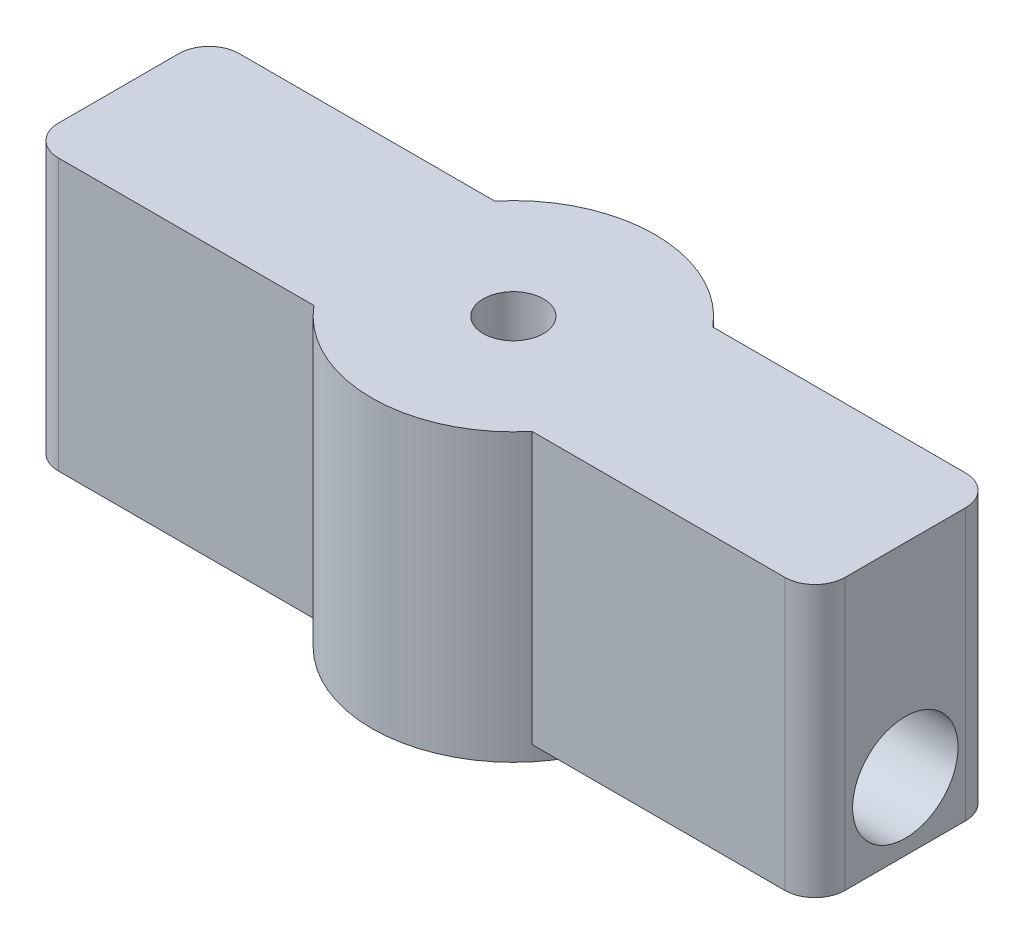
SolidWorks part; units mm, degrees
ref_plane "Front Plane" through (0, 0, 0) normal (0, 0, 1) x (1, 0, 0)
ref_plane "Top Plane" through (0, 0, 0) normal (0, 1, 0) x (1, 0, 0)
ref_plane "Right Plane" through (0, 0, 0) normal (1, 0, 0) x (0, 0, -1)
sketch "Sketch1" plane through (0, 0, 0) normal (0, 1, 0) x (1, 0, 0)
  circle A0 centre (0, 0) radius 2.5
  circle A1 centre (0, 0) radius 4.7
  dimension "D1" = 5
  dimension "D2" = 2.2
extrude "Boss-Extrude1" add sketch "Sketch1" along normal blind 5
sketch "Sketch2" plane through (0, 5, 0) normal (0, 1, 0) x (1, 0, 0)
  circle A0 centre (0, 0) radius 4.7
  circle A1 centre (0, 0) radius 4.7 construction
  dimension "D1" = 0
extrude "Boss-Extrude2" add sketch "Sketch2" along normal blind 4.5
sketch "Sketch3" plane through (0, 9.5, 0) normal (0, 1, 0) x (1, 0, 0)
  circle A0 centre (0, 0) radius 1
  dimension "D1" = 2
extrude "Cut-Extrude1" cut sketch "Sketch3" against normal blind 4.5
ref_plane "Plane1" through (4.7, 0, 0) normal (1, 0, 0) x (0, 0, -1)
sketch "Sketch6" plane through (4.7, 0, 0) normal (1, 0, 0) x (0, 0, -1)
  line L1 (3, 6.5) -> (-3, 6.5)
  line L2 (3, 6.5) -> (3, 0.5)
  line L3 (3, 0.5) -> (-3, 0.5)
  line L4 (-3, 6.5) -> (-3, 0.5)
  line L6 (-2.5, 0) -> (2.5, 0) construction
  line L7 (4.7, 9.5) -> (-4.7, 9.5) construction
  line L8 (4.7, 0) -> (4.7, 9.5) construction
  line L9 (-4.7, 9.5) -> (-4.7, 0) construction
  dimension "D1" = 6
  dimension "D2" = 6
  dimension "D3" = 1.7
  dimension "D4" = 1.7
  dimension "D5" = 0.5
  dimension "D6" = 3
extrude "Boss-Extrude3" add sketch "Sketch6" along normal blind 8.31 separate body
sketch "Sketch7" plane through (4.7, 0, 0) normal (-1, 0, 0) x (0, 0, 1)
  line L4 (-3, 6.5) -> (-3, 0.5)
  line L5 (-3, 0.5) -> (3, 0.5)
  line L6 (3, 0.5) -> (3, 6.5)
  line L7 (3, 6.5) -> (-3, 6.5)
  line L8 (-3, 6.5) -> (-3, 0.5)
  line L9 (-3, 0.5) -> (3, 0.5)
  line L10 (3, 0.5) -> (3, 6.5)
  line L11 (3, 6.5) -> (-3, 6.5)
  dimension "D1" = 0
extrude "Boss-Extrude4" add sketch "Sketch7" along normal blind 2
fillet "Fillet1" radius 1 2 edges at (13.01, 3.5, -3) (13.01, 3.5, 3)
sketch "Sketch8" plane through (13.01, 0, 0) normal (1, 0, 0) x (0, 0, -1)
  line L0 (-3, 6.5) -> (-3, 0.5) construction
  line L1 (3, 0.5) -> (3, 6.5) construction
  line L2 (2, 6.5) -> (-2, 6.5) construction
  line L3 (-2, 0.5) -> (2, 0.5) construction
  circle A0 centre (0, 2.75) radius 1.75
  dimension "D1" = 3.5
  dimension "D2" = 3
  dimension "D3" = 3
  dimension "D5" = 2.25
  dimension "D4" = 3.75
sketch "Sketch9" plane through (0, 6.5, 0) normal (0, 1, 0) x (1, 0, 0)
  line L3 (13.01, -2) -> (13.01, 2)
  line L4 (12.01, 3) -> (3.618, 3)
  line L5 (3.618, -3) -> (12.01, -3)
  line L6 (13.01, -2) -> (13.01, 2)
  line L7 (12.01, 3) -> (3.618, 3)
  line L8 (3.618, -3) -> (12.01, -3)
  arc A3 (13.01, 2) -> (12.01, 3) centre (12.01, 2) ccw
  arc A4 (3.618, -3) -> (3.618, 3) centre (0, 0) ccw
  arc A5 (12.01, -3) -> (13.01, -2) centre (12.01, -2) ccw
  arc A6 (13.01, 2) -> (12.01, 3) centre (12.01, 2) ccw
  arc A7 (3.618, -3) -> (3.618, 3) centre (0, 0) ccw
  arc A8 (12.01, -3) -> (13.01, -2) centre (12.01, -2) ccw
  dimension "D1" = 0
extrude "Boss-Extrude5" add sketch "Sketch9" along normal up to surface (3 mm away) up to face at (0, 9.5, 1)
sketch "Sketch10" plane through (0, 9.5, 0) normal (0, 1, 0) x (1, 0, 0)
  line L1 (3.618, -3) -> (-13.1, -3)
  line L2 (3.618, -3) -> (3.618, 3)
  line L3 (3.618, 3) -> (-13.1, 3)
  line L4 (-13.1, -3) -> (-13.1, 3)
  circle A0 centre (0, 0) radius 4.5
  arc M6 (3.618, 3) -> (3.618, -3) centre (0, 0) ccw
  dimension "D2" = 9
  dimension "D1" = 13.1
extrude "Boss-Extrude6" add sketch "Sketch10" against normal up to surface (9 mm away) contours L4 L1 L3 M6
fillet "Fillet2" radius 1 2 edges at (-13.1, 5, 3) (-13.1, 5, -3)
extrude "Cut-Extrude6" cut sketch "Sketch8" against normal blind 37 contours A0
sketch "Sketch14" plane through (13.01, 0, 0) normal (1, 0, 0) x (0, 0, -1)
  line L1 (0, 2.75) -> (1.8416, 2.75)
  line L2 (0, 2.75) -> (0, 5.3563)
  line L3 (0, 5.3563) -> (1.8416, 5.3563)
  line L4 (1.8416, 2.75) -> (1.8416, 5.3563)
  circle A0 centre (0, 2.75) radius 1.75 construction
  circle A1 centre (0, 2.75) radius 1.75
